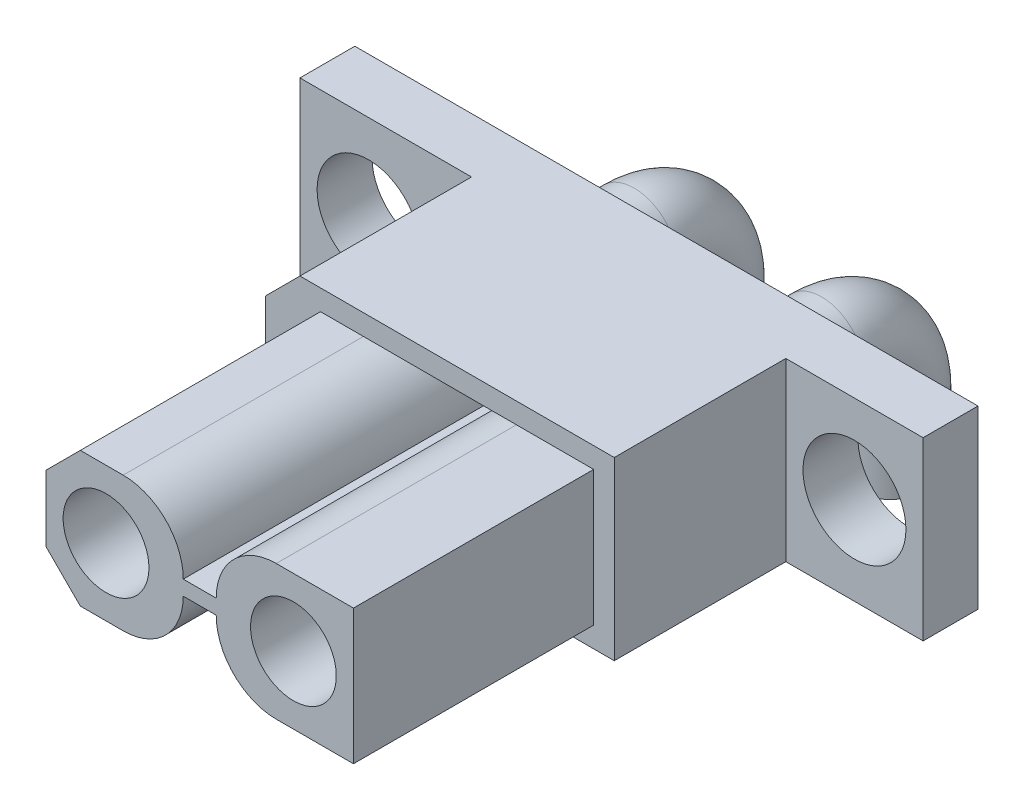
SolidWorks part; units mm, degrees
material "2A12"
ref_plane "前视基准面" through (0, 0, 0) normal (0, 0, 1) x (1, 0, 0)
ref_plane "上视基准面" through (0, 0, 0) normal (0, 1, 0) x (1, 0, 0)
ref_plane "右视基准面" through (0, 0, 0) normal (1, 0, 0) x (0, 0, -1)
sketch "草图1" plane through (0, 0, 0) normal (0, 0, 1) x (1, 0, 0)
  line L0 (-5.08, 1.565) -> (-4.08, 2.565)
  line L1 (-4.08, 2.565) -> (5.08, 2.565)
  line L2 (-5.08, 1.565) -> (-5.08, -1.565)
  line L3 (-4.08, -2.565) -> (5.08, -2.565)
  line L4 (5.08, 2.565) -> (5.08, -2.565)
  line L5 (-5.08, 2.565) -> (5.08, -2.565) construction
  line L6 (-5.08, -2.565) -> (5.08, 2.565) construction
  line L7 (-5.08, -1.565) -> (-4.08, -2.565)
  line L9 (-2.58, 1.965) -> (4.48, 1.965)
  line L10 (-4.48, 0.065) -> (-4.48, -0.065)
  line L11 (-2.58, -1.965) -> (4.48, -1.965)
  line L12 (4.48, 1.965) -> (4.48, -1.965)
  line L13 (-4.48, 1.965) -> (4.48, -1.965) construction
  line L14 (-4.48, -1.965) -> (4.48, 1.965) construction
  arc A0 (-4.48, -0.065) -> (-2.58, -1.965) centre (-2.58, -0.065) ccw
  arc A1 (-4.48, 0.065) -> (-2.58, 1.965) centre (-2.58, 0.065) cw
  point P0 (0, 0)
  point P10 (0, 0)
  dimension "D5" = 1.9
  dimension "D1" = 5.13
  dimension "D2" = 10.16
  dimension "D3" = 0.6
  dimension "D4" = 0.6
extrude "凸台-拉伸1" add sketch "草图1" along normal blind 5
ref_plane "基准面1" through (0, 0, 12) normal (0, 0, 1) x (1, 0, 0)
sketch "草图11" plane through (0, 0, 12) normal (0, 0, 1) x (1, 0, 0)
  line L1 (-2.58, -1.965) -> (4.48, -1.965) construction
  line L2 (4.48, 1.965) -> (2.23, 1.965)
  line L3 (4.48, 1.965) -> (4.48, -1.965)
  line L4 (4.48, -1.965) -> (2.23, -1.965)
  line L6 (0, 0) -> (0, -1.965) construction
  line L7 (-3.48, 1.965) -> (-2.23, 1.965)
  line L8 (-4.48, 0.965) -> (-4.48, -0.965)
  line L9 (-3.48, -1.965) -> (-2.23, -1.965)
  line L11 (-4.48, 0.965) -> (-3.48, 1.965)
  line L12 (-4.48, -0.965) -> (-3.48, -1.965)
  line L13 (-0.48, 0.215) -> (0.48, 0.215)
  line L14 (-0.48, -0.215) -> (0.48, -0.215)
  arc A0 (2.23, -1.965) -> (0.48, -0.215) centre (2.23, -0.215) cw
  arc A1 (0.48, 0.215) -> (2.23, 1.965) centre (2.23, 0.215) cw
  arc A2 (-2.23, -1.965) -> (-0.48, -0.215) centre (-2.23, -0.215) ccw
  arc A3 (-0.48, 0.215) -> (-2.23, 1.965) centre (-2.23, 0.215) ccw
  point P10 (0.48, -1.965)
  point P13 (0.48, 1.965)
  point P17 (-4.48, 1.965)
  point P19 (-4.48, -1.965)
  dimension "D2" = 1.75
  dimension "D1" = 4
extrude "凸台-拉伸2" add sketch "草图11" against normal blind 9
sketch "草图12" plane through (0, 0, 12) normal (0, 0, 1) x (1, 0, 0)
  line L0 (-4.48, 0) -> (4.48, 0) construction
  line L1 (-4.48, 0.965) -> (-4.48, -0.965) construction
  line L2 (4.48, -1.965) -> (4.48, 1.965) construction
  line L3 (0, 1.965) -> (0, -1.965) construction
  line L4 (2.23, 1.965) -> (-2.23, 1.965) construction
  line L5 (-2.23, -1.965) -> (2.23, -1.965) construction
  circle A0 centre (-2.73, 0) radius 1.25
  circle A1 centre (2.73, 0) radius 1.25
  dimension "D1" = 2.73
extrude "切除-拉伸3" cut sketch "草图12" against normal blind 7
sketch "草图13" plane through (0, 0, 3) normal (0, 0, -1) x (-1, 0, 0)
  line L0 (0, 0) -> (-2.73, 0) construction
  circle A0 centre (-2.73, 0) radius 1.25
  circle A1 centre (2.73, 0) radius 1.25
  dimension "D2" = 2.5
  dimension "D3" = 2.73
  dimension "D1" = 2.73
extrude "凸台-拉伸3" add sketch "草图13" along normal blind 5.5
sketch "草图14" plane through (0, 0, -2.5) normal (0, 0, -1) x (-1, 0, 0)
  line L0 (2.73, 1.25) -> (2.73, 1.05)
  line L1 (2.73, -1.05) -> (2.73, -1.25)
  line L2 (0, 0) -> (0, 0.9343) construction
  line L3 (-2.73, -1.05) -> (-2.73, -1.25)
  line L4 (-2.73, 1.25) -> (-2.73, 1.05)
  arc A0 (2.73, 1.25) -> (2.73, -1.25) centre (2.73, 0) ccw
  arc A1 (2.73, 1.05) -> (2.73, -1.05) centre (2.73, 0) ccw
  arc A2 (-2.73, 1.05) -> (-2.73, -1.05) centre (-2.73, 0) cw
  circle A3 centre (2.73, 0) radius 1.05 construction
  circle A4 centre (2.73, 0) radius 1.25 construction
  arc A5 (-2.73, 1.25) -> (-2.73, -1.25) centre (-2.73, 0) cw
  point P4 (3.9254, 0.3655)
  point P7 (3.78, 0)
  dimension "D1" = 0.2
extrude "切除-拉伸4" cut sketch "草图14" against normal blind 2 flip side to cut
sketch "草图15" plane through (0, -2.565, 0) normal (0, -1, 0) x (1, 0, 0)
  text T0 "X130" font "汉仪长仿宋体" height in points 9
extrude "凸台-拉伸4" add sketch "草图15" along normal blind 0.2
sketch "草图16" plane through (0, 0, 0) normal (0, 0, -1) x (-1, 0, 0)
  line L1 (-9.08, 2.565) -> (9.08, 2.565)
  line L2 (-9.08, 2.565) -> (-9.08, -2.565)
  line L3 (-9.08, -2.565) -> (9.08, -2.565)
  line L4 (9.08, 2.565) -> (9.08, -2.565)
  line L5 (-5.08, 2.565) -> (4.08, 2.565) construction
  line L6 (4.08, -2.565) -> (-5.08, -2.565) construction
  line L7 (-5.08, -2.565) -> (-5.08, 2.565) construction
  line L8 (5.08, 1.565) -> (5.08, -1.565) construction
  dimension "D1" = 4
  dimension "D2" = 4
extrude "凸台-拉伸5" add sketch "草图16" along normal blind 1.6
sketch "草图17" plane through (0, 0, 0) normal (0, 0, 1) x (1, 0, 0)
  line L0 (9.08, 2.565) -> (5.08, -2.565) construction
  circle A0 centre (7.08, 0) radius 1.5
  dimension "D1" = 3
extrude "切除-拉伸5" cut sketch "草图17" against normal blind 1.6
mirror "镜向1" about plane through (0, 0, 0) normal (1, 0, 0) of "切除-拉伸5"
sketch "草图18" plane through (0, 0, -1.6) normal (0, 0, -1) x (-1, 0, 0)
  line L0 (-9.08, -2.565) -> (9.08, -2.565) construction
  line L1 (-9.08, 2.565) -> (-4.08, 2.565)
  line L2 (-9.08, 2.565) -> (-9.08, -2.565)
  line L3 (-9.08, -2.565) -> (-4.08, -2.565)
  line L4 (-4.08, 2.565) -> (-4.08, -2.565)
  line L6 (9.08, 2.565) -> (4.08, 2.565)
  line L7 (9.08, 2.565) -> (9.08, -2.565)
  line L8 (9.08, -2.565) -> (4.08, -2.565)
  line L9 (4.08, 2.565) -> (4.08, -2.565)
  dimension "D1" = 5
extrude "凸台-拉伸6" [suppressed] add sketch "草图18" along normal blind 3
sketch "草图19" [suppressed] plane through (0, 0, -4.6) normal (0, 0, -1) x (-1, 0, 0)
  line L1 (-9.08, 2.565) -> (9.08, 2.565)
  line L2 (-9.08, 2.565) -> (-9.08, -2.565)
  line L3 (-9.08, -2.565) -> (9.08, -2.565)
  line L4 (9.08, 2.565) -> (9.08, -2.565)
extrude "凸台-拉伸7" [suppressed] add sketch "草图19" along normal blind 3
sketch "草图20" [suppressed] plane through (0, -2.565, 0) normal (0, -1, 0) x (1, 0, 0)
  line L1 (9.08, -7.6) -> (-9.08, -7.6) construction
  line L2 (6.5, -11.6) -> (-6.5, -11.6) construction
  line L3 (6.5, -11.6) -> (6.5, -3.6) construction
  line L4 (6.5, -3.6) -> (-6.5, -3.6) construction
  line L5 (-6.5, -11.6) -> (-6.5, -3.6) construction
  line L6 (6.5, -11.6) -> (-6.5, -3.6) construction
  line L7 (6.5, -3.6) -> (-6.5, -11.6) construction
  circle A0 centre (-6.5, -3.6) radius 1.25
  circle A1 centre (6.5, -3.6) radius 1.25
  point P7 (0, -7.6)
  dimension "D1" = 2.5
  dimension "D2" = 13
  dimension "D3" = 4
extrude "凸台-拉伸8" [suppressed] add sketch "草图20" along normal blind 2
sketch "草图21" plane through (0, 2.565, 0) normal (0, 1, 0) x (1, 0, 0)
  line L0 (-9.08, 1.6) -> (-9.08, 0) construction
  line L1 (-9.08, 1.6) -> (9.08, 1.6)
  line L2 (-9.08, 1.6) -> (-9.08, 1.7)
  line L3 (-9.08, 1.7) -> (9.08, 1.7)
  line L4 (9.08, 1.6) -> (9.08, 1.7)
  line L5 (9.08, 1.6) -> (9.08, 0) construction
  dimension "D1" = 0.1
extrude "切除-拉伸6" cut sketch "草图21" against normal blind 19
sketch "草图22" plane through (0, 0, -1.6) normal (0, 0, -1) x (-1, 0, 0)
  circle A0 centre (-2.73, 0) radius 1.25
  circle A1 centre (2.73, 0) radius 1.265
sketch "草图23" plane through (0, 0, 0) normal (1, 0, 0) x (0, 0, -1)
  line L0 (1.6, 0) -> (3.391, 0)
  line L1 (1.6, -1.25) -> (1.6, 1.25) construction
  line L2 (5.391, -2) -> (5.391, -3.9812)
  arc A0 (5.391, -2) -> (3.391, 0) centre (3.391, -2) ccw
  dimension "D1" = 2
sweep "扫描1" add profiles "草图22" path "草图23"
